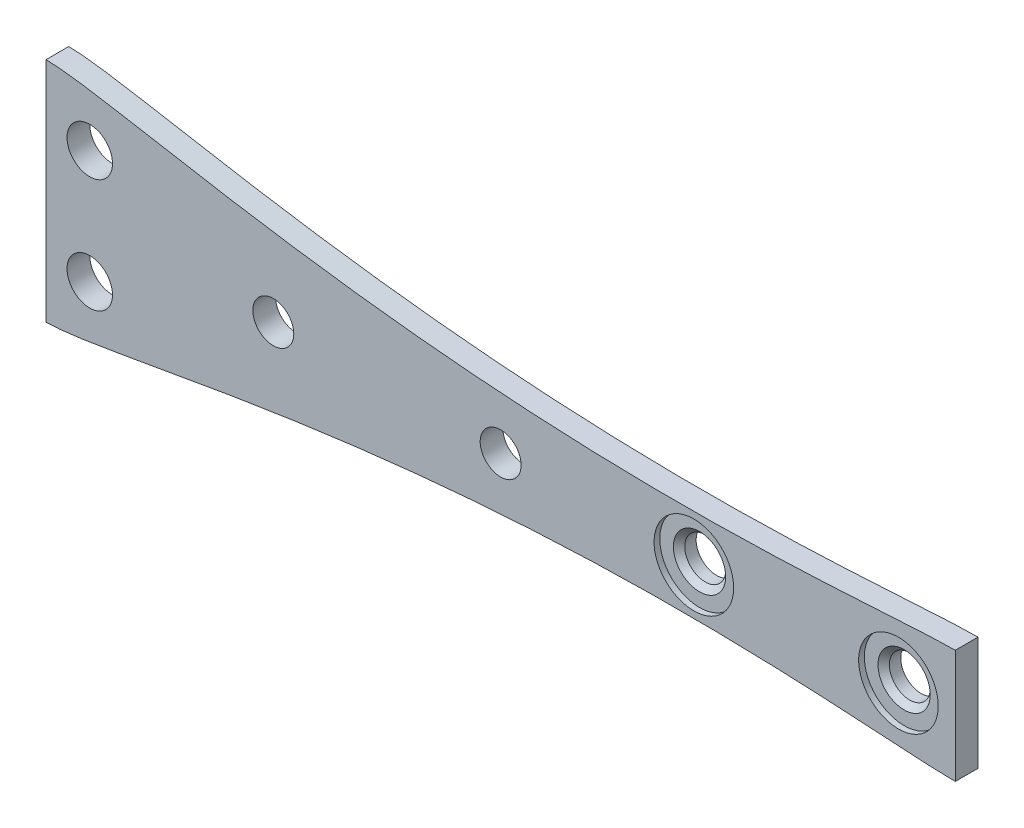
SolidWorks part; units mm, degrees
ref_plane "Plan de face" through (0, 0, 0) normal (0, 0, 1) x (1, 0, 0)
ref_plane "Plan de dessus" through (0, 0, 0) normal (0, 1, 0) x (1, 0, 0)
ref_plane "Plan de droite" through (0, 0, 0) normal (1, 0, 0) x (0, 0, -1)
sketch "Esquisse1" plane through (0, 0, 0) normal (0, 0, 1) x (1, 0, 0)
  line L0 (0, 0) -> (0, 20)
  line L1 (0, 0) -> (8, 0)
  line L2 (0, 20) -> (8, 20)
  line L3 (8, 0) -> (8, 20)
  line L4 (8, 15) -> (70, 15)
  line L5 (8, 15) -> (8, 5)
  line L6 (70, 15) -> (70, 5)
  line L7 (8, 5) -> (70, 5)
  line L8 (80, 15) -> (70, 15)
  line L9 (80, 15) -> (80, 5)
  line L10 (70, 15) -> (70, 5)
  line L11 (80, 5) -> (70, 5)
  line L12 (8, 10) -> (70, 10) construction
  line L13 (0, 20) -> (8, 20) construction
  line L14 (8, 20) -> (39, 10) construction
  line L15 (39, 10) -> (70, 15) construction
  line L16 (70, 15) -> (80, 15) construction
  line L17 (0, 0) -> (8, 0) construction
  line L18 (8, 0) -> (39, 10) construction
  line L19 (39, 10) -> (70, 5) construction
  line L20 (70, 5) -> (80, 5) construction
  circle A0 centre (3.85, 15) radius 2
  circle A1 centre (3.85, 5) radius 2
  circle A2 centre (57, 10) radius 1.8
  circle A3 centre (75, 10) radius 1.8
  circle A4 centre (20, 10) radius 1.8
  circle A5 centre (40, 10) radius 1.8
  spline S0 degree 4 poles (0, 20) (8, 20) (39, 10) (70, 15) (80, 15) knots 0 0 0 0 0 1 1 1 1 1
  spline S1 degree 4 poles (0, 0) (8, 0) (39, 10) (70, 5) (80, 5) knots 0 0 0 0 0 1 1 1 1 1
  point P0 (70, 10)
  point P12 (70, 10)
  point P16 (8, 10)
  point P17 (8, 10)
  point P43 (39, 10)
  point P44 (80, 10)
  dimension "D8" = 4
  dimension "D9" = 4
  dimension "D14" = 3.6
  dimension "D15" = 3.6
  dimension "D19" = 3.6
  dimension "D20" = 3.6
  dimension "D1" = 8
  dimension "D2" = 20
  dimension "D3" = 10
  dimension "D4" = 10
  dimension "D5" = 10
  dimension "D6" = 80
  dimension "D7" = 10
  dimension "D10" = 3.85
  dimension "D11" = 3.85
  dimension "D12" = 5
  dimension "D13" = 18
  dimension "D16" = 5
  dimension "D17" = 5
  dimension "D18" = 5
  dimension "D21" = 20
  dimension "D22" = 5
  dimension "D23" = 5
  dimension "D24" = 30
extrude "Boss.-Extru.1" add sketch "Esquisse1" along normal blind 2 contours L0 S1 L3 S0 A1 A0 | L7 S1 L10 S0 L4 L3 A5 A4 A2 | S0 L3 L4 | L3 S1 L7 | L10 S1 L9 S0 A3
sketch "Esquisse3" plane through (0, 0, 2) normal (0, 0, 1) x (1, 0, 0)
  circle A0 centre (57, 10) radius 3.5
  circle A1 centre (75, 10) radius 3.5
  dimension "D1" = 7
  dimension "D2" = 7
extrude "Enlèv. mat.-Extru.1" cut sketch "Esquisse3" against normal blind 0.5
chamfer "Chanfrein1" distance 0.5 angle 45 2 edges at (76.8, 10, 1.5) (58.8, 10, 1.5)
